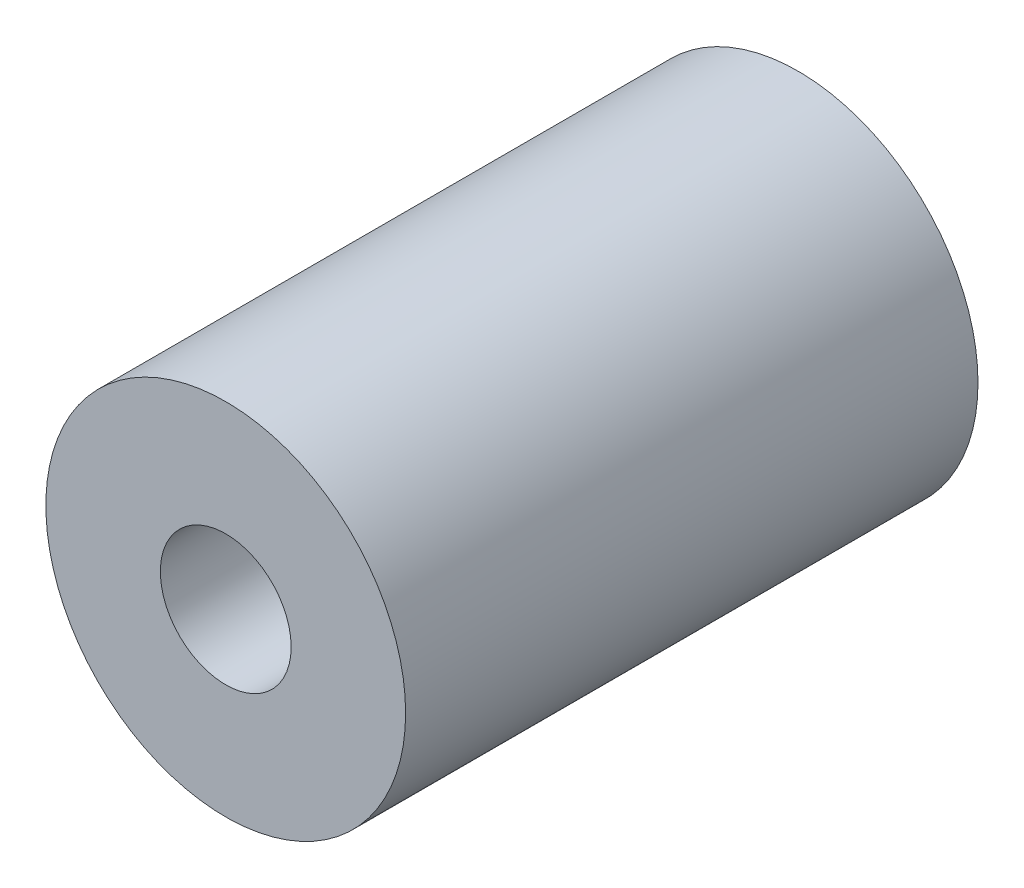
SolidWorks part; units mm, degrees
ref_plane "前视基准面" through (0, 0, 0) normal (0, 0, 1) x (1, 0, 0)
ref_plane "上视基准面" through (0, 0, 0) normal (0, 1, 0) x (1, 0, 0)
ref_plane "右视基准面" through (0, 0, 0) normal (1, 0, 0) x (0, 0, -1)
sketch "草图3" plane through (0, 0, 0) normal (0, 0, 1) x (1, 0, 0)
  circle A0 centre (0, 0) radius 11
  dimension "D1" = 22
extrude "凸台-拉伸2" add sketch "草图3" along normal blind 35
sketch "草图4" plane through (0, 0, 35) normal (0, 0, 1) x (1, 0, 0)
  circle A0 centre (0, 0) radius 4
  dimension "D1" = 8
extrude "切除-拉伸1" cut sketch "草图4" against normal blind 35
sketch "草图5" plane through (0, 0, 0) normal (0, 1, 0) x (1, 0, 0)
  circle A0 centre (0, -6.7636) radius 2
  circle A1 centre (0, -28.0344) radius 2
  dimension "D1" = 4
  dimension "D2" = 4
extrude "切除-拉伸2" cut sketch "草图5" against normal blind 35
